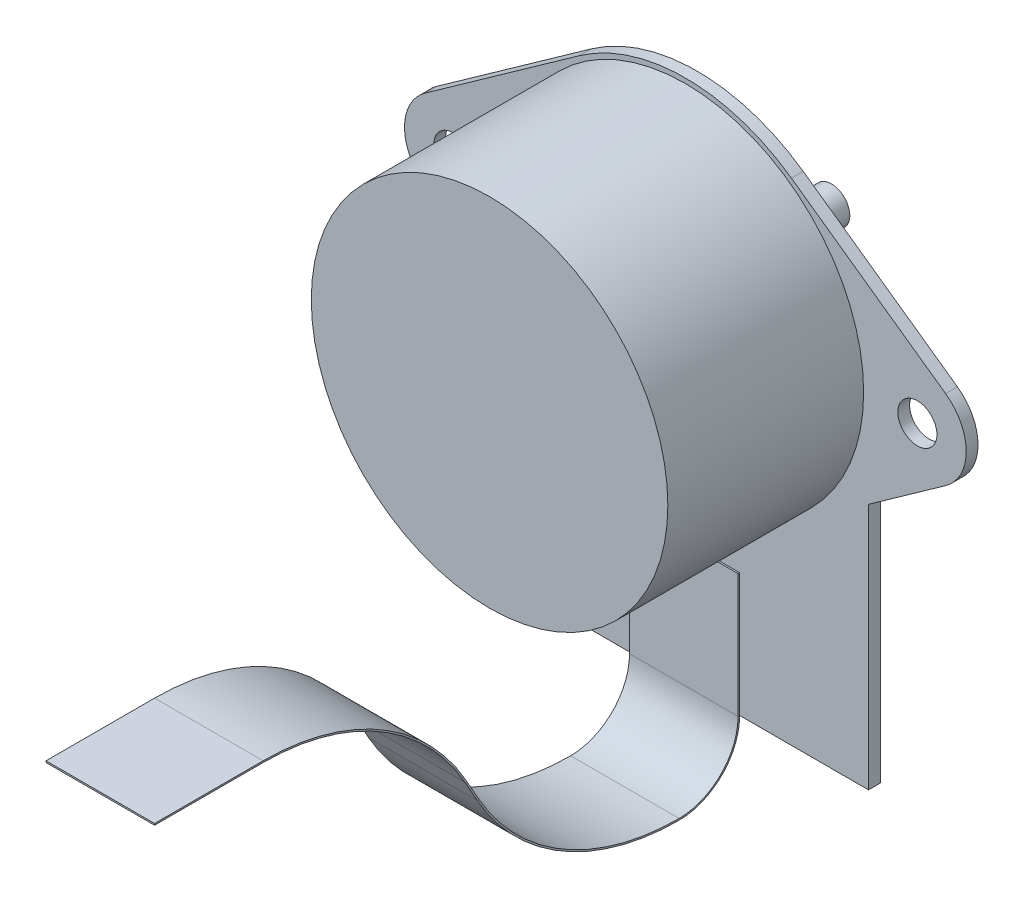
SolidWorks part; units mm, degrees
material "Plain Carbon Steel"
ref_plane "Front Plane" through (0, 0, 0) normal (0, 0, 1) x (1, 0, 0)
ref_plane "Top Plane" through (0, 0, 0) normal (0, 1, 0) x (1, 0, 0)
ref_plane "Right Plane" through (0, 0, 0) normal (1, 0, 0) x (0, 0, -1)
sketch "Sketch1" plane through (0, 0, 0) normal (0, 0, 1) x (1, 0, 0)
  circle A0 centre (0, 0) radius 15
  dimension "D1" = 30
extrude "Boss-Extrude1" add sketch "Sketch1" along normal blind 0.9652
sketch "Sketch2" plane through (0, 0, 0.9652) normal (0, 0, 1) x (1, 0, 0)
  line L0 (0, 0) -> (0, 50000) construction
  line L1 (-21.3158, 3.2615) -> (-8.6842, 12.2305)
  line L2 (0, 0) -> (50000, 0) construction
  line L3 (-21.3158, -3.2615) -> (-8.6842, -12.2305)
  line L4 (21.3158, -3.2615) -> (8.6842, -12.2305)
  line L5 (21.3158, 3.2615) -> (8.6842, 12.2305)
  circle A0 centre (-19, 0) radius 1.6
  circle A1 centre (19, 0) radius 1.6
  arc A2 (-21.3158, 3.2615) -> (-21.3158, -3.2615) centre (-19, 0) ccw
  circle A3 centre (0, 0) radius 15 construction
  arc A4 (21.3158, 3.2615) -> (21.3158, -3.2615) centre (19, 0) cw
  arc A5 (-8.6842, 12.2305) -> (8.6842, 12.2305) centre (0, 0) cw
  arc A6 (-8.6842, -12.2305) -> (8.6842, -12.2305) centre (0, 0) ccw
  point P22 (8.6205, -12.2754)
  dimension "D1" = 3.2
  dimension "D3" = 4
  dimension "D2" = 38
extrude "Boss-Extrude2" add sketch "Sketch2" against normal through all
sketch "Sketch3" plane through (0, 0, 0.9652) normal (0, 0, 1) x (1, 0, 0)
  line L1 (15, -28) -> (-15, -28)
  line L2 (15, -28) -> (15, -2)
  line L3 (15, -2) -> (-15, -2)
  line L4 (-15, -28) -> (-15, -2)
  line L5 (15, -28) -> (-15, -2) construction
  line L6 (15, -2) -> (-15, -28) construction
  arc A0 (-8.6842, -12.2305) -> (8.6842, -12.2305) centre (0, 0) ccw construction
  point P0 (0, -15)
  dimension "D1" = 28
  dimension "D2" = 30
extrude "Boss-Extrude3" add sketch "Sketch3" against normal through all
sketch "Sketch4" plane through (0, 0, 0.9652) normal (0, 0, 1) x (1, 0, 0)
  circle A0 centre (0, 0) radius 14.6
  dimension "D1" = 29.2
extrude "Boss-Extrude4" add sketch "Sketch4" along normal offset from surface (16.0348 mm away) 17 up to face at (0, -4.4261, 0)
sketch "Sketch5" plane through (0, 0, 0) normal (0, 0, -1) x (-1, 0, 0)
  circle A0 centre (0, 0) radius 1.5
  dimension "D1" = 3
extrude "Boss-Extrude5" add sketch "Sketch5" along normal blind 11
sketch "Sketch6" plane through (0, 0, 0) normal (0, 0, -1) x (-1, 0, 0)
  circle A0 centre (0, 0) radius 7
  dimension "D1" = 14
extrude "Boss-Extrude6" add sketch "Sketch6" along normal blind 2
sketch "Sketch7" plane through (0, 0, 0) normal (1, 0, 0) x (0, 0, -1)
  line L0 (-0.9652, -7.746) -> (-0.9652, -28) construction
  line L1 (-48.8799, -11.826) -> (-39.9899, -11.826)
  line L2 (-48.8799, -11.326) -> (-48.8799, -11.926) construction
  line L3 (-48.8799, -11.699) -> (-39.9899, -11.699)
  line L4 (-48.7799, -11.826) -> (-46.4299, -11.826) construction
  line L8 (-23.3543, -21.4204) -> (-22.3325, -23.2339)
  line L9 (-0.9652, -28) -> (-0.9652, -17.873)
  line L12 (-23.4649, -21.4827) -> (-22.4431, -23.2963)
  line L13 (-1.0922, -28) -> (-1.0922, -17.873)
  line L14 (-1.0922, -17.873) -> (-0.9652, -17.873)
  line L15 (-48.8799, -11.699) -> (-48.8799, -11.826)
  arc A4 (-0.9652, -28) -> (-5.9182, -32.953) centre (-5.9182, -28) cw
  arc A5 (-5.9182, -32.953) -> (-22.4431, -23.2963) centre (-5.9182, -13.9856) cw
  arc A6 (-39.9899, -11.826) -> (-23.4649, -21.4827) centre (-39.9899, -30.7934) cw
  arc A7 (-39.9899, -11.699) -> (-23.3543, -21.4204) centre (-39.9899, -30.7934) cw
  arc A8 (-5.9182, -32.826) -> (-22.3325, -23.2339) centre (-5.9182, -13.9856) cw
  arc A9 (-1.0922, -28) -> (-5.9182, -32.826) centre (-5.9182, -28) cw
  point P1 (-14.5948, -29.8888)
  point P3 (-13.8033, -29.7981)
  point P11 (-12.5235, -30.3515)
  point P12 (-17.232, -28.0073)
  point P13 (-5.7277, -32.6355)
  point P14 (-18.9264, -27.0382)
  point P17 (-20.1892, -26.0522)
  point P18 (-21.7179, -24.5803)
  point P19 (-22.7185, -23.3339)
  dimension "D1" = 8.89
  dimension "D3" = 4.953
  dimension "D4" = 0.127
extrude "Boss-Extrude7" add sketch "Sketch7" along normal mid plane 8.89
